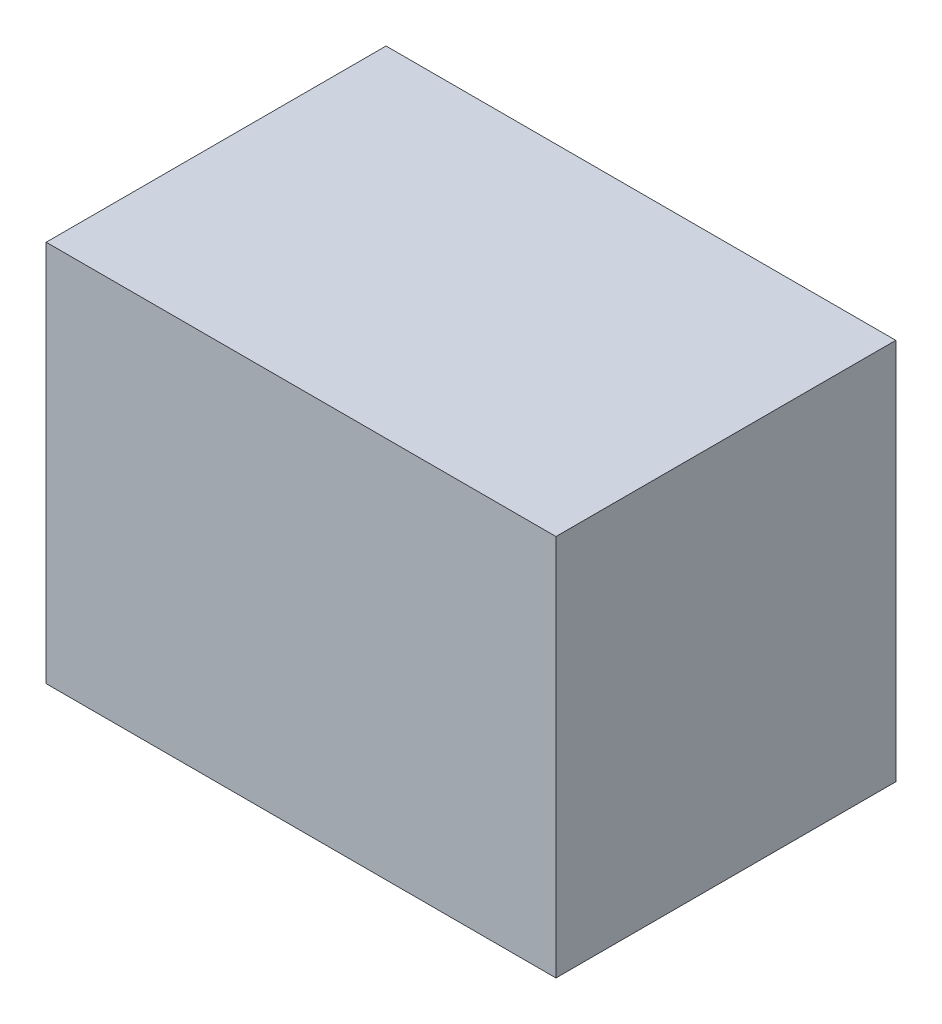
SolidWorks part; units mm, degrees
ref_plane "前视基准面" through (0, 0, 0) normal (0, 0, 1) x (1, 0, 0)
ref_plane "上视基准面" through (0, 0, 0) normal (0, 1, 0) x (1, 0, 0)
ref_plane "右视基准面" through (0, 0, 0) normal (1, 0, 0) x (0, 0, -1)
other "Configuration Table"
sketch "草图1" plane through (0, 0, 0) normal (0, 1, 0) x (1, 0, 0)
  line L1 (-30, 20) -> (30, 20)
  line L2 (-30, 20) -> (-30, -20)
  line L3 (-30, -20) -> (30, -20)
  line L4 (30, 20) -> (30, -20)
  line L5 (-30, 20) -> (30, -20) construction
  line L6 (-30, -20) -> (30, 20) construction
  point P0 (0, 0)
  dimension "D1" = 40
  dimension "D2" = 60
extrude "凸台-拉伸1" add sketch "草图1" along normal blind 45
